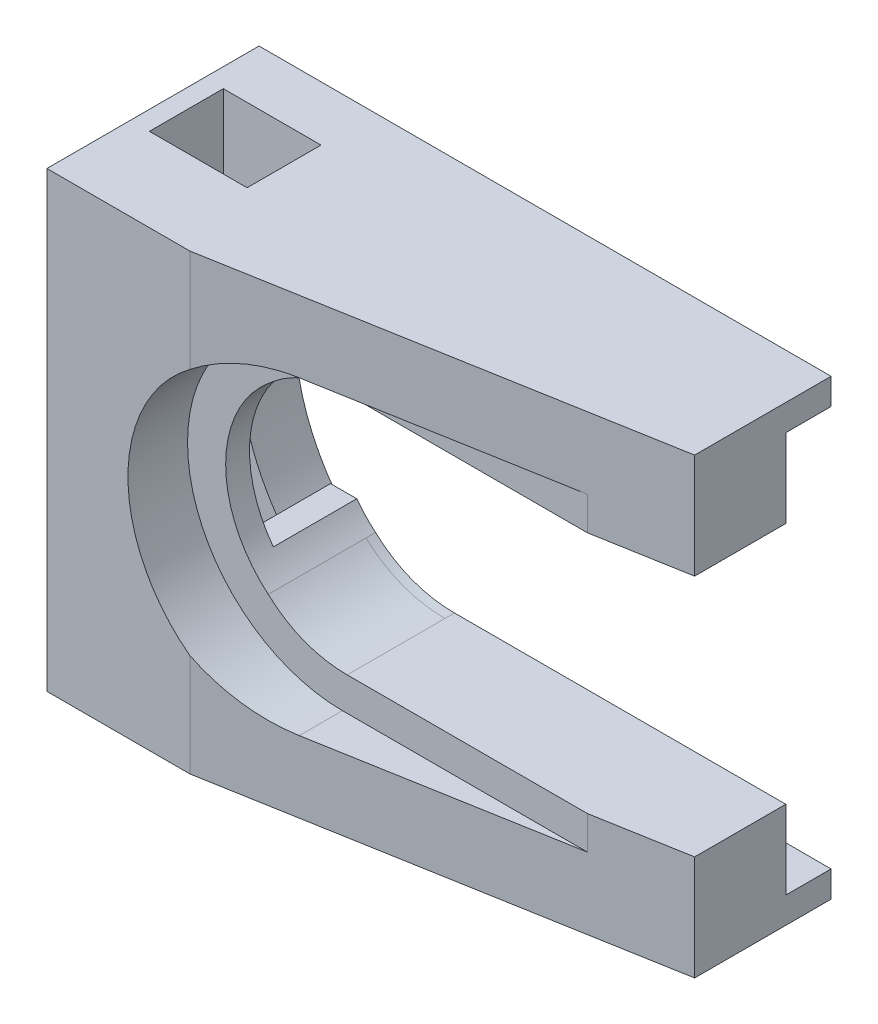
SolidWorks part; units mm, degrees
other "标注1"
sketch "草图10" plane through (24, 9.5, 31.5) normal (0.9281, 0.3391, 0.154) x (-0.3723, 0.8344, 0.4063)
other "标注2"
sketch "草图11" plane through (24, 9.5, 31.5) normal (0.9281, 0.3391, 0.154) x (-0.3723, 0.8344, 0.4063)
ref_plane "前视基准面" through (0, 0, 0) normal (1, 0, 0) x (0, 1, 0)
ref_plane "上视基准面" through (0, 0, 0) normal (0, 0, 1) x (0, 1, 0)
ref_plane "右视基准面" through (0, 0, 0) normal (0, 1, 0) x (-1, 0, 0)
other "Configuration Table"
sketch "1底部方形_24x19" plane through (0, 0, 0) normal (0, 0, 1) x (0, 1, 0)
  line L1 (-9.5, 12) -> (9.5, 12)
  line L2 (-9.5, 12) -> (-9.5, -12)
  line L3 (-9.5, -12) -> (9.5, -12)
  line L4 (9.5, 12) -> (9.5, -12)
  line L5 (0, -12) -> (0, 12) construction
  line L6 (-9.5, 0) -> (9.5, 0) construction
  point P0 (0, 0)
  dimension "D1" = 19
  dimension "D2" = 24
extrude "1凸台-拉伸_高33" add sketch "1底部方形_24x19" along normal blind 33
sketch "2吸嘴停靠渐变槽" plane through (0, 0, 33) normal (0, 0, 1) x (1, 0, 0)
  line L0 (12, -9.5) -> (12, 9.5) construction
  line L1 (-12, 9.5) -> (-12, -9.5) construction
  line L2 (12, -5.1) -> (12, 5.1)
  line L3 (-12, 9.5) -> (-12, -9.5) construction
  line L4 (-12, 0) -> (12, 0) construction
  line L5 (-1.9, 5.1) -> (12, 5.1)
  line L6 (-1.9, -5.1) -> (12, -5.1)
  line L7 (-5.2139, -3.8302) -> (-2, 0) construction
  line L8 (-5.2139, 3.8302) -> (-2, 0) construction
  line L9 (-4.0554, -4.6222) -> (-1.9, 0) construction
  line L10 (-1.9, 0) -> (-4.0554, 4.6222) construction
  arc A0 (-1.9, 5.1) -> (-1.9, -5.1) centre (-1.9, 0) ccw construction
  arc A1 (-5.2139, 3.8302) -> (-5.2139, -3.8302) centre (-2, 0) ccw
  circle A2 centre (-1.9, 0) radius 5.1 construction
  spline S0 degree 2 poles (-5.2139, 3.8302) (-3.8291, 5.0932) (-1.9, 5.1) knots 0 0 0 1 1 1
  spline S1 degree 2 poles (-5.2139, -3.8302) (-3.8291, -5.0932) (-1.9, -5.1) knots 0 0 0 1 1 1
  point P7 (-7, 0)
  point P14 (-5.2139, 3.8302)
  point P15 (-4.0554, 4.6222)
  point P16 (-4.0554, -4.6222)
  point P17 (-5.2139, -3.8302)
  dimension "D1" = 10.2
  dimension "D4" = 10
  dimension "D2" = 5
  dimension "D3" = 10.1
  dimension "D5" = 0.1
  dimension "D6" = 50
  dimension "D7" = 50
  dimension "D8" = 65
  dimension "D9" = 65
  dimension "D10" = 10.2
extrude "2切除-拉伸" cut sketch "2吸嘴停靠渐变槽" against normal up to next
ref_plane "3基准面1" through (0, 0, 25) normal (0, 0, 1) x (1, 0, 0)
sketch "4反光板停靠槽" plane through (0, 0, 25) normal (0, 0, 1) x (1, 0, 0)
  line L18 (-12, 9.5) -> (12, 9.5) construction
  line L22 (-0.7, 8.4) -> (12, 8.4)
  line L23 (12, -9.5) -> (12, 9.5) construction
  line L24 (-0.7, -8.4) -> (12, -8.4)
  line L25 (12, 8.4) -> (12, -8.4)
  line L27 (12, 0) -> (-12, 0) construction
  line L28 (-12, -9.5) -> (12, -9.5) construction
  arc A2 (-0.7, 8.4) -> (-0.7, -8.4) centre (-2, 0) ccw
  arc A5 (-5.2139, 3.8302) -> (-5.2139, -3.8302) centre (-2, 0) ccw construction
  arc A6 (-5.2139, 3.8302) -> (-5.2139, -3.8302) centre (-2, 0) ccw construction
  dimension "D1" = 9.5
  dimension "D2" = 17
  dimension "D5" = 8.4
  dimension "D6" = 5
  dimension "D7" = 9.5
  dimension "D3" = 16.8
  dimension "D4" = 8.4
extrude "4切除-拉伸2" cut sketch "4反光板停靠槽" against normal blind 1.9 contours L22 L25 L24 A2
ref_plane "5基准面_反光板下表面" through (0, 0, 23.1) normal (0, 0, 1) x (1, 0, 0)
sketch "6反光板小圆柱" plane through (0, 0, 23.1) normal (0, 0, 1) x (1, 0, 0)
  line L1 (-2.1, -6.3) -> (12, -6.3)
  line L5 (-2.1, 5.1) -> (-2.1, -5.1) construction
  line L6 (-2.1, 6.3) -> (12, 6.3)
  line L7 (12, 5.1) -> (12, 9.5) construction
  line L8 (12, 6.3) -> (12, -6.3)
  arc A2 (-2.1, 6.3) -> (-2.1, -6.3) centre (-2.1, 0) ccw
  point P0 (-2.1, 0)
  point P2 (-2, 0)
  point P13 (12, 0)
  dimension "D1" = 6.3
  dimension "D3" = 0.1
  dimension "D2" = 12.6
  dimension "D4" = 6.3
extrude "6切除-拉伸3" cut sketch "6反光板小圆柱" against normal up to next
sketch "7草图5" plane through (0, 0, 0) normal (0, 0, -1) x (1, 0, 0)
  line L0 (12, -9.5) -> (-12, -9.5) construction
  line L1 (-12, -9.5) -> (-12, 9.5) construction
  line L2 (-12, 9.5) -> (12, 9.5) construction
  line L3 (12, -9.5) -> (-12, -9.5)
  line L4 (-12, -9.5) -> (-12, 9.5)
  line L5 (-12, 9.5) -> (12, 9.5)
  line L6 (12, 9.5) -> (12, -9.5)
extrude "7凸台-拉伸_底板厚度" add sketch "7草图5" against normal blind 5
sketch "8中轴面" plane through (-12, 0, 0) normal (-1, 0, 0) x (0, -1, 0)
  line L0 (0, 33) -> (0, 0) construction
  line L1 (-9.5, 33) -> (9.5, 33) construction
  line L2 (-9.5, 0) -> (9.5, 0) construction
ref_plane "9中轴基准面" through (0, 0, 0) normal (0, 1, 0) x (1, 0, 0)
sketch "10设计脱离斜坡" plane through (0, 9.5, 0) normal (0, 1, 0) x (-1, 0, 0)
  line L2 (-12, 33) -> (-12, 0) construction
  line L3 (12, 33) -> (12, 0) construction
  line L5 (-12, 31.1627) -> (-12, 33)
  line L6 (10.45, 25) -> (-10.45, 25) construction
  line L9 (9, 33) -> (-12, 33)
  line L10 (-12, 31.1627) -> (9, 33)
  line L11 (-12, 33) -> (12, 33) construction
  dimension "D1" = 5
  dimension "D2" = 3
  dimension "D3" = 1.8373
  dimension "D4" = 24
  dimension "D5" = 6.1627
extrude "10切除-拉伸4" cut sketch "10设计脱离斜坡" against normal up to surface (19 mm away) up to face at (0, -9.5, 16.5)
sketch "11磁铁高度" plane through (-12, 0, 0) normal (-1, 0, 0) x (0, -1, 0)
  line L0 (-9.5, 33) -> (-9.5, 0) construction
  line L1 (-9.5, 28.5) -> (-1, 28.5)
  line L2 (-9.5, 28.5) -> (-9.5, 25.4)
  line L3 (-9.5, 25.4) -> (-1, 25.4)
  line L4 (9.5, 28.5) -> (9.5, 25.4)
  line L5 (-9.5, 28.5) -> (9.5, 25.4) construction
  line L6 (-9.5, 25.4) -> (9.5, 28.5) construction
  line L7 (9.5, 33) -> (9.5, 0) construction
  line L8 (-1, 28.5) -> (-1, 25.4)
  line L9 (1, 28.5) -> (1, 25.4)
  line L10 (1, 28.5) -> (9.5, 28.5)
  line L11 (1, 25.4) -> (9.5, 25.4)
  line L15 (9.5, 0) -> (-9.5, 0) construction
  point P4 (0, 26.95)
  dimension "D1" = 28.5
  dimension "D2" = 3.1
  dimension "D3" = 1
  dimension "D4" = 1
extrude "11切除-拉伸5" cut sketch "11磁铁高度" against normal blind 4.9
sketch "11d1_磁铁开窗" plane through (-12, 0, 0) normal (-1, 0, 0) x (0, -1, 0)
  line L0 (1, 25.4) -> (9.5, 25.4) construction
  line L5 (-1, 28.5) -> (1, 25.4) construction
  line L7 (1, 28.5) -> (1, 25.4) construction
  line L8 (9.5, 28.5) -> (1, 28.5) construction
  line L9 (-3, 25.4) -> (3, 25.4)
  line L10 (-3, 25.4) -> (-3, 28.5)
  line L11 (-3, 28.5) -> (3, 28.5)
  line L12 (3, 25.4) -> (3, 28.5)
  line L13 (0, 28.5) -> (0, 25.4) construction
  line L14 (-3, 26.95) -> (3, 26.95) construction
  point P10 (0, 26.95)
  dimension "D1" = 6
extrude "11d1切除-拉伸6" cut sketch "11d1_磁铁开窗" against normal blind 10
sketch "12切除薄壁" plane through (0, 0, 25.4) normal (0, 0, 1) x (1, 0, 0)
  line L43 (-0.7, 8.4) -> (-0.7, -8.4)
  arc A0 (-0.7, 8.4) -> (-0.7, -8.4) centre (-2, 0) ccw construction
  arc A7 (-0.7, 8.4) -> (-0.7, -8.4) centre (-2, 0) ccw
extrude "12切除-拉伸9" cut sketch "12切除薄壁" against normal up to next
sketch "螺丝安装孔" plane through (0, 0, 5) normal (0, 0, 1) x (1, 0, 0)
  line L0 (13.2, 0) -> (-13.2, 0) construction
  line L1 (12, 6.3) -> (12, -6.3) construction
  circle A0 centre (2, 0) radius 3.5
  dimension "D1" = 10
  dimension "D2" = 7
sketch "设计内套槽" plane through (0, 0, 33) normal (0, 0, 1) x (1, 0, 0)
  line L0 (-2.1, 6.5) -> (12, 6.5)
  line L2 (-2.1, -6.5) -> (12, -6.5)
  line L4 (12, 6.5) -> (12, -6.5)
  line L5 (12, -9.5) -> (12, 9.5) construction
  arc A1 (-1.4745, -4.9607) -> (-1.4745, 4.9607) centre (-2.1, 0) ccw construction
  arc A2 (-2.1, 6.5) -> (-2.1, -6.5) centre (-2.1, 0) ccw
  point P4 (-2.1, 0)
  point P8 (-2, 0)
  dimension "D1" = 13
  dimension "D4" = 6.5
  dimension "D6" = 5
  dimension "D5" = 0.1
  dimension "D2" = 6.5
  dimension "D3" = 6.5
extrude "切除-拉伸11" cut sketch "设计内套槽" against normal blind 3.5 contours L0 A2 L2 L4
sketch "实际高度" plane through (0, 0, 33) normal (0, 0, 1) x (1, 0, 0)
  line L0 (-9, -9.5) -> (-9, 9.5) construction
  line L1 (41.98, 9.5) -> (-12, 9.5)
  line L2 (41.98, 9.5) -> (41.98, -9.5)
  line L3 (41.98, -9.5) -> (-12, -9.5)
  line L4 (-12, 9.5) -> (-12, -9.5)
  line L5 (41.98, 9.5) -> (-12, -9.5) construction
  line L6 (41.98, -9.5) -> (-12, 9.5) construction
  line L7 (-9, 9.5) -> (-12, 9.5) construction
  point P4 (14.99, 0)
  dimension "D1" = 23.99
extrude "切除-拉伸12" cut sketch "实际高度" against normal blind 1
sketch "实际脱离斜坡" plane through (0, -9.5, 0) normal (0, -1, 0) x (1, 0, 0)
  line L0 (2.4301, 32) -> (12, 31.1627) construction
  line L1 (2.4301, 32) -> (12, 31.1627)
  line L3 (-6, 32) -> (12, 28.8261)
  line L5 (-12, 32) -> (2.4301, 32) construction
  line L6 (12, 31.1627) -> (12, 0) construction
  line L7 (10.45, 25) -> (-10.45, 25) construction
  line L9 (-12, 33) -> (-12, 0) construction
  line L11 (12, 28.8261) -> (12, 31.1627)
  line L12 (2.4301, 32) -> (-6, 32)
  dimension "D1" = 6
  dimension "D2" = 10
  dimension "D3" = 3.8261
  dimension "D4" = 3.1739
  dimension "D5" = 18
extrude "切除-拉伸13" cut sketch "实际脱离斜坡" against normal through all
extrude "切除-拉伸15" cut sketch "螺丝安装孔" against normal up to next contours A0
sketch "退刀中心位置" plane through (0, 0, 5) normal (0, 0, 1) x (1, 0, 0)
  line L0 (12, -9.5) -> (12, 9.5) construction
  line L1 (12, -9.5) -> (12, 9.5) construction
  line L2 (12, 0) -> (-12, 0) construction
  line L3 (27.5479, 0) -> (-12, 0) construction
  line L4 (13.2, 0) -> (-13.2, 0) construction
  line L5 (20, 0) -> (20, -11.3299) construction
  circle A0 centre (20, 0) radius 8 construction
  dimension "D2" = 16
  dimension "D1" = 8
sketch "反光板槽_补缺" plane through (0, 0, 25.4) normal (0, 0, -1) x (1, 0, 0)
  line L0 (-7.1, -3) -> (-7.1, -6.8) construction
  line L1 (-0.7, -8.4) -> (-0.7, -5.1) construction
  line L2 (-0.7, -5.1) -> (-1.9, -5.1) construction
  line L3 (-6, -3) -> (-7.1, -3) construction
  line L4 (-7.1, 3) -> (-6, 3) construction
  line L5 (-1.9, 5.1) -> (-0.7, 5.1) construction
  line L6 (-0.7, 5.1) -> (-0.7, 8.4) construction
  line L7 (-7.1, 6.8) -> (-7.1, 3) construction
  line L8 (-7.1, -3) -> (-7.1, -6.8)
  line L9 (-0.7, -8.4) -> (-0.7, -5.1)
  line L10 (-0.7, -5.1) -> (-1.9, -5.1)
  line L11 (-6, -3) -> (-7.1, -3)
  line L12 (-7.1, 3) -> (-6, 3)
  line L13 (-1.9, 5.1) -> (-0.7, 5.1)
  line L14 (-0.7, 5.1) -> (-0.7, 8.4)
  line L15 (-7.1, 6.8) -> (-7.1, 3)
  arc A0 (-7.1, -6.8) -> (-0.7, -8.4) centre (-2, 0) ccw construction
  arc A1 (-6, -3) -> (-5.2139, -3.8302) centre (-2, 0) ccw construction
  arc A2 (-5.2139, 3.8302) -> (-6, 3) centre (-2, 0) ccw construction
  arc A3 (-0.7, 8.4) -> (-7.1, 6.8) centre (-2, 0) ccw construction
  arc A4 (-7.1, -6.8) -> (-0.7, -8.4) centre (-2, 0) ccw
  arc A5 (-6, -3) -> (-5.2139, -3.8302) centre (-2, 0) ccw
  arc A6 (-5.2139, 3.8302) -> (-6, 3) centre (-2, 0) ccw
  arc A7 (-0.7, 8.4) -> (-7.1, 6.8) centre (-2, 0) ccw
  parabola Q0 (-1.9, -5.1) -> (-5.2139, -3.8302) focus (-2.9632, -2.5982) apex (-3.8759, -4.7046) construction
  parabola Q1 (-5.2139, 3.8302) -> (-1.9, 5.1) focus (-2.9632, 2.5982) apex (-3.8759, 4.7046) construction
  parabola Q2 (-1.9, -5.1) -> (-5.2139, -3.8302) focus (-2.9632, -2.5982) apex (-3.8759, -4.7046)
  parabola Q3 (-5.2139, 3.8302) -> (-1.9, 5.1) focus (-2.9632, 2.5982) apex (-3.8759, 4.7046)
extrude "凸台-拉伸2" add sketch "反光板槽_补缺" along normal up to surface (0.4 mm away) up to face at (5.65, 6.75, 25)
sketch "磁铁宽度挡板" plane through (0, -9.5, 0) normal (0, -1, 0) x (1, 0, 0)
  line L0 (-7.1, 25.4) -> (-12, 25.4) construction
  line L1 (-12, 28.5) -> (-11.2, 28.5)
  line L2 (-12, 28.5) -> (-12, 25.4)
  line L3 (-12, 25.4) -> (-11.2, 25.4)
  line L4 (-11.2, 28.5) -> (-11.2, 25.4)
  line L5 (-12, 28.5) -> (-11.2, 25.4) construction
  line L6 (-12, 25.4) -> (-11.2, 28.5) construction
  line L7 (-7.1, 25.4) -> (-7.1, 28.5) construction
  point P4 (-11.6, 26.95)
  dimension "D1" = 4.1
  dimension "D2" = 0.8
extrude "凸台-拉伸3" add sketch "磁铁宽度挡板" against normal up to surface (19 mm away) up to face at (-4.9111, 9.5, 22.2918)
sketch "草图13" plane through (0, 0, 5) normal (0, 0, 1) x (1, 0, 0)
  line L3 (-2.1, -6.3) -> (12, -6.3)
  line L4 (12, -6.3) -> (12, 6.3)
  line L5 (12, 6.3) -> (-2.1, 6.3)
  line L6 (-2.1, -6.3) -> (12, -6.3)
  line L7 (12, -6.3) -> (12, 6.3)
  line L8 (12, 6.3) -> (-2.1, 6.3)
  arc A1 (-2.1, 6.3) -> (-2.1, -6.3) centre (-2.1, 0) ccw
  arc A2 (-2.1, 6.3) -> (-2.1, -6.3) centre (-2.1, 0) ccw
  dimension "D1" = 0
extrude "切除-拉伸16" cut sketch "草图13" against normal through all
sketch "草图14" plane through (0, 0, 23.1) normal (0, 0, 1) x (1, 0, 0)
  line L1 (-20.5643, 15.2546) -> (33.4538, 15.2546)
  line L2 (-20.5643, 15.2546) -> (-20.5643, -14.6723)
  line L3 (-20.5643, -14.6723) -> (33.4538, -14.6723)
  line L4 (33.4538, 15.2546) -> (33.4538, -14.6723)
extrude "切除-拉伸17" cut sketch "草图14" against normal through all
